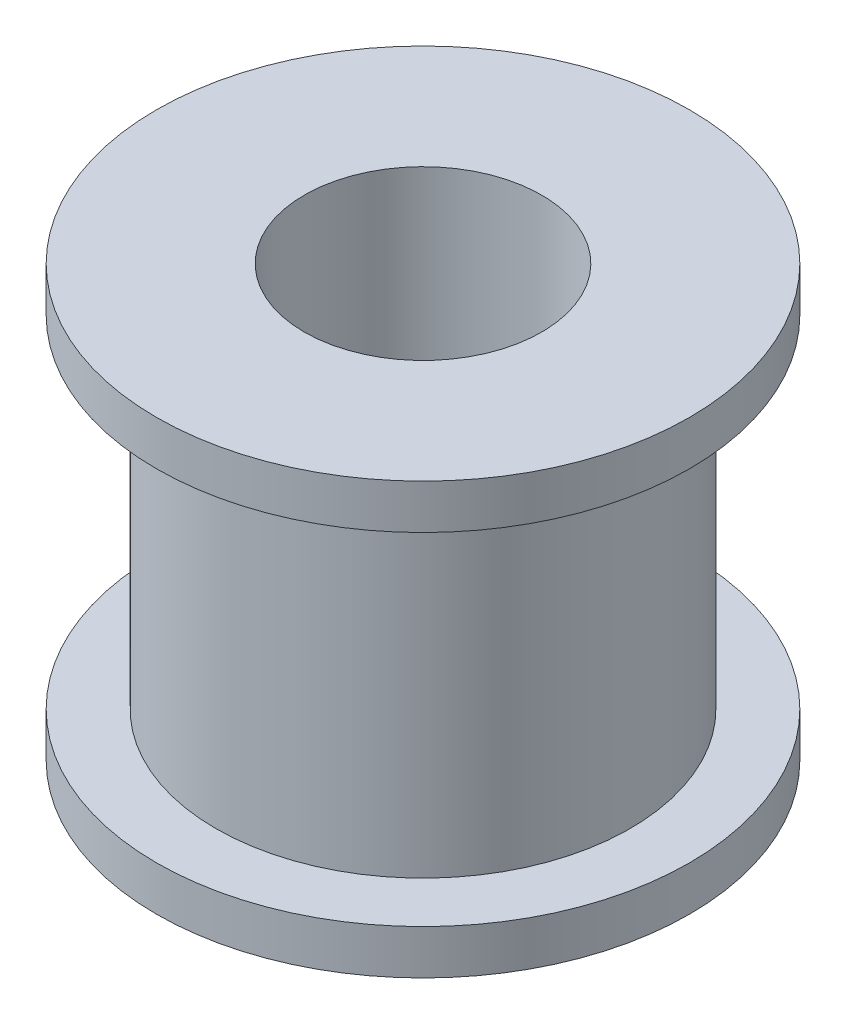
SolidWorks part; units mm, degrees
ref_plane "Front" through (0, 0, 0) normal (0, 0, 1) x (1, 0, 0)
ref_plane "Top" through (0, 0, 0) normal (0, 1, 0) x (1, 0, 0)
ref_plane "Right" through (0, 0, 0) normal (1, 0, 0) x (0, 0, -1)
sketch "Sketch1" plane through (0, 0, 0) normal (1, 0, 0) x (0, 0, -1)
  line L0 (0, 10.3155) -> (0, -12.6924) construction
  line L1 (-13.3377, 0) -> (15.1571, 0) construction
  line L2 (6.98, -5.75) -> (6.98, 5.75)
  line L3 (8.98, 5.75) -> (8.98, 7.25)
  line L4 (8.98, 7.25) -> (4, 7.25)
  line L5 (6.98, 5.75) -> (8.98, 5.75)
  line L6 (4, 7.25) -> (4, -7.25)
  line L7 (6.98, -5.75) -> (8.98, -5.75)
  line L8 (8.98, -5.75) -> (8.98, -7.25)
  line L9 (8.98, -7.25) -> (4, -7.25)
  point P11 (6.98, 0)
  point P15 (4, 0)
  dimension "D1" = 1.5
  dimension "D2" = 7.25
  dimension "D3" = 8.98
  dimension "D4" = 2
  dimension "2" = 4
revolve "Revolve1" add sketch "Sketch1" angle 360 about L0
sketch "Sketch2" [suppressed] plane through (0, 7, 0) normal (0, 1, 0) x (1, 0, 0)
  line L0 (0, 0) -> (-8.713, 0) construction
  line L1 (-2.8, -1) -> (-5, -1)
  line L2 (-2.8, -1) -> (-2.8, 1)
  line L3 (-2.8, 1) -> (-5, 1)
  line L4 (-5, -1) -> (-5, 1)
  point P7 (-5, 0)
  dimension "D1" = 2
  dimension "D2" = 2.2
  dimension "D3" = 2.8
extrude "Cut-Extrude1" [suppressed] cut sketch "Sketch2" against normal through all
sketch "Sketch3" plane through (0, -7.25, 0) normal (0, -1, 0) x (1, 0, 0)
  circle A0 centre (0, 0) radius 4 construction
  circle A1 centre (0, 0) radius 4
  circle A2 centre (0, 0) radius 5
  dimension "10" = 10
extrude "Cut-Extrude2" [suppressed] cut sketch "Sketch3" against normal through all
